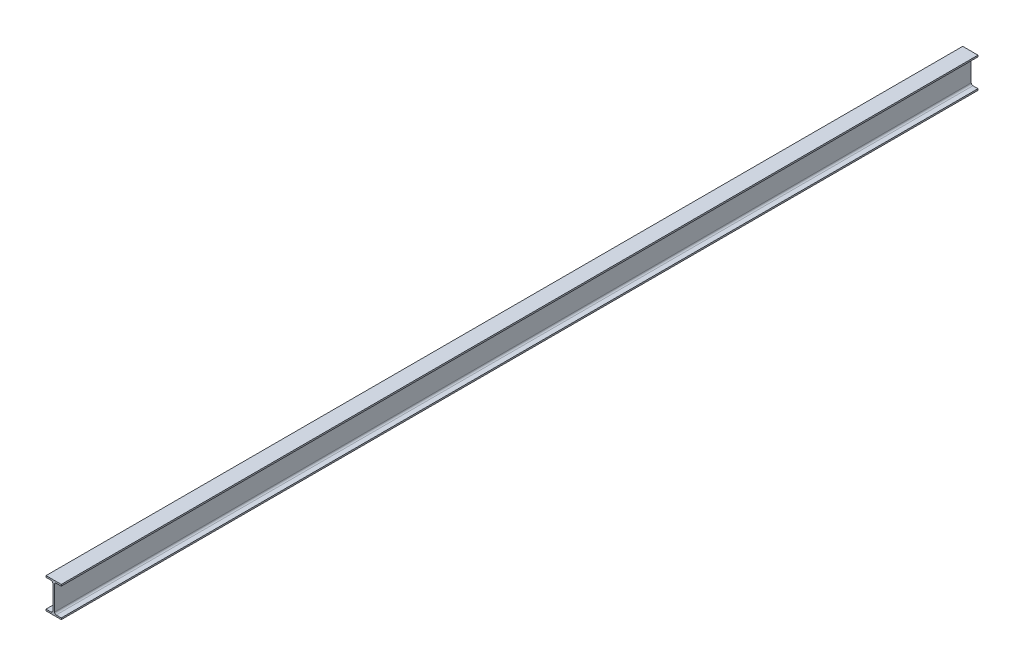
SolidWorks part; units mm, degrees
ref_plane "Front Plane" through (0, 0, 0) normal (0, 0, 1) x (1, 0, 0)
ref_plane "Top Plane" through (0, 0, 0) normal (0, 1, 0) x (1, 0, 0)
ref_plane "Right Plane" through (0, 0, 0) normal (1, 0, 0) x (0, 0, -1)
sketch "Sketch1" plane through (0, 0, 0) normal (0, 0, 1) x (1, 0, 0)
  line L3 (5.7, 0) -> (5.7, 79)
  line L4 (5.7, 0) -> (5.7, -79)
  line L6 (-5.7, 0) -> (-5.7, 79)
  line L7 (-5.7, 0) -> (-5.7, -79)
  line L8 (16.7, 90) -> (50, 90)
  line L9 (50, 90) -> (50, 100)
  line L10 (50, 100) -> (-50, 100)
  line L11 (-50, 100) -> (-50, 90)
  line L12 (-50, 90) -> (-16.7, 90)
  line L13 (-16.7, -90) -> (-50, -90)
  line L14 (-50, -90) -> (-50, -100)
  line L15 (-50, -100) -> (50, -100)
  line L16 (50, -100) -> (50, -90)
  line L17 (50, -90) -> (16.7, -90)
  arc A0 (16.7, -90) -> (5.7, -79) centre (16.7, -79) cw
  arc A1 (-16.7, -90) -> (-5.7, -79) centre (-16.7, -79) ccw
  arc A2 (16.7, 90) -> (5.7, 79) centre (16.7, 79) ccw
  arc A3 (-5.7, 79) -> (-16.7, 90) centre (-16.7, 79) ccw
  dimension "D1" = 11
extrude "Boss-Extrude1" add sketch "Sketch1" along normal mid plane 6000
